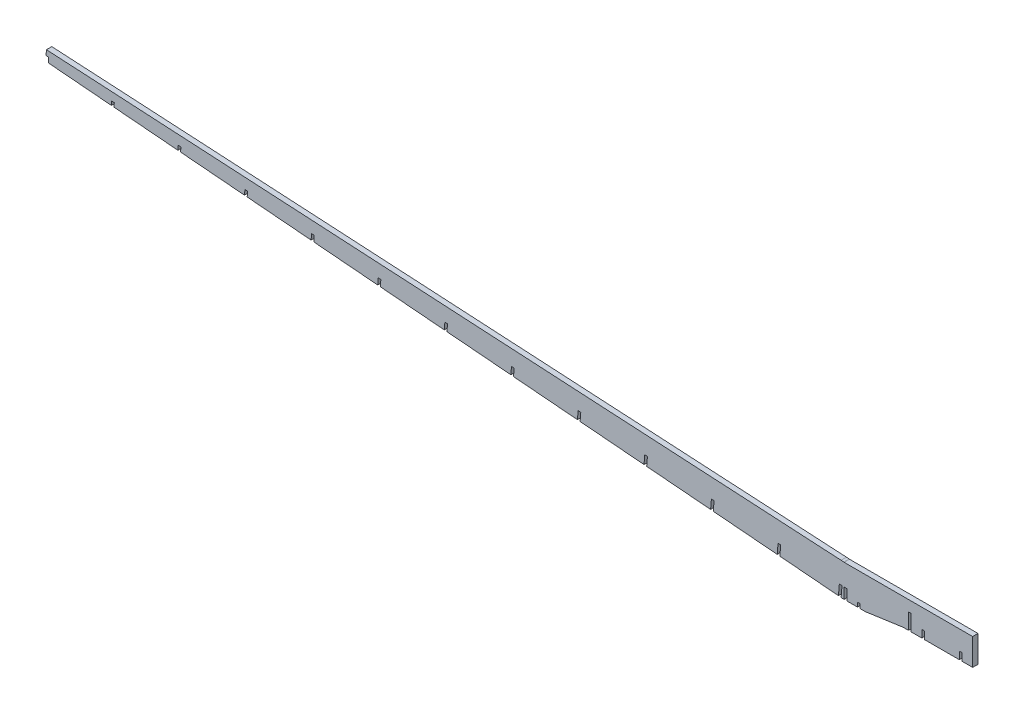
SolidWorks part; units mm, degrees
material "Balsa"
ref_plane "Front Plane" through (0, 0, 0) normal (0, 0, 1) x (1, 0, 0)
ref_plane "Top Plane" through (0, 0, 0) normal (0, 1, 0) x (1, 0, 0)
ref_plane "Right Plane" through (0, 0, 0) normal (1, 0, 0) x (0, 0, -1)
sketch "Sketch1" plane through (0, 0, 0) normal (0, 0, 1) x (1, 0, 0)
  line L0 (76.2, 56.7475) -> (76.2, 37.6975)
  line L1 (79.375, 56.7475) -> (79.375, 37.6975)
  line L2 (0, 44.0475) -> (0, 31.3475)
  line L3 (3.175, 44.0475) -> (3.175, 31.3475)
  line L4 (-5.7133, 44.4467) -> (-6.776, 31.7912)
  line L5 (-2.5494, 44.181) -> (-3.6121, 31.5255)
  line L6 (-1.4923, 31.3475) -> (25.4, 31.3475)
  line L7 (25.4, 31.3475) -> (69.85, 37.6975)
  line L8 (-2.5494, 44.181) -> (-0.424, 69.4919) construction
  line L9 (-0.424, 69.4919) -> (-3.5879, 69.7576)
  line L10 (-3.5879, 69.7576) -> (-5.7133, 44.4467) construction
  line L11 (-5.7133, 44.4467) -> (-2.5494, 44.181)
  line L12 (3.175, 44.0475) -> (3.175, 69.4475) construction
  line L13 (3.175, 69.4475) -> (0, 69.4475)
  line L14 (0, 69.4475) -> (0, 44.0475) construction
  line L15 (0, 44.0475) -> (3.175, 44.0475)
  line L16 (92.075, 37.6975) -> (92.075, 46.5875)
  line L17 (-942.8808, 122.7744) -> (-947.5199, 67.5279)
  line L18 (0, 69.4475) -> (-0.424, 69.4919)
  line L19 (3.175, 69.4475) -> (152.4, 69.4475)
  line L20 (152.4, 69.4475) -> (152.4, 37.6975)
  line L21 (152.4, 37.6975) -> (69.85, 37.6975)
  line L22 (92.075, 46.5875) -> (95.25, 46.5875)
  line L23 (95.25, 46.5875) -> (95.25, 37.6975)
  line L24 (-1.4923, 31.3475) -> (-943.9128, 110.4848)
  line L25 (79.375, 69.4475) -> (79.375, 56.7475)
  line L26 (-942.8808, 122.7744) -> (-3.5879, 69.7576)
  line L27 (136.525, 37.6975) -> (136.525, 46.5875)
  line L28 (76.2, 69.4475) -> (76.2, 56.7475)
  line L29 (79.375, 56.7475) -> (76.2, 56.7475)
  line L30 (-943.5688, 114.5813) -> (-5.7133, 44.4467)
  line L31 (136.525, 46.5875) -> (139.7, 46.5875)
  line L32 (139.7, 46.5875) -> (139.7, 37.6975)
  line L33 (15.875, 31.3475) -> (15.875, 36.4275)
  line L34 (15.875, 36.4275) -> (19.05, 36.4275)
  line L35 (19.05, 36.4275) -> (19.05, 31.3475)
  line L36 (-942.8808, 122.7744) -> (-946.0519, 122.9534)
  line L37 (-946.0519, 122.9534) -> (-946.5835, 116.6233)
  line L38 (-946.5835, 116.6233) -> (-943.4123, 116.4443)
  dimension "D3" = 76.2
  dimension "D10" = 12.3329
  dimension "D11" = 8.2219
  dimension "D2" = 25.4
  dimension "D4" = 25.4
  dimension "D5" = 12.7
  dimension "D7" = 3.175
  dimension "D9" = 3.175
  dimension "D12" = 3.175
  dimension "D6" = 19.05
  dimension "D13" = 6.35
  dimension "D14" = 12.7
  dimension "D16" = 3.175
  dimension "D17" = 3.175
  dimension "D18" = 12.7
  dimension "D19" = 12.7
  dimension "D20" = 8.89
  dimension "D21" = 8.89
  dimension "D15" = 76.2
  dimension "D22" = 12.7
  dimension "D23" = 3.175
  dimension "D24" = 5.08
  dimension "D8" = 6.35
  dimension "D25" = 3.175
  dimension "D26" = 6.35
extrude "Boss-Extrude1" add sketch "Sketch1" along normal mid plane 6.35 contours L17 L30 L11 L5 L24 L6 L2 L15 L3 L7 L21 L0 L28 L19 L13 L18 L9 L26 | L30 L17 L24 L4 | L29 L25 L19 L28 | L19 L25 L1 L21 L20 | L37 L38 L17 L36
sketch "Sketch2" plane through (0, 0, 3.175) normal (0, 0, 1) x (1, 0, 0)
  line L2 (-73.2652, 73.2231) -> (-80.3969, -11.7061)
  line L3 (-943.5688, 114.5813) -> (-5.7133, 44.4467)
  line L6 (-76.4291, 73.4888) -> (-83.5608, -11.4404)
  line L7 (-6.776, 31.7912) -> (-943.9128, 110.4848)
  line L10 (-152.4177, 77.6821) -> (-159.3225, -4.5442)
  line L14 (-155.5816, 77.9478) -> (-162.4863, -4.2785)
  line L18 (-231.5658, 82.1932) -> (-238.251, 2.5812)
  line L22 (-234.7297, 82.4589) -> (-241.4149, 2.8469)
  line L26 (-310.7178, 86.6582) -> (-317.1769, 9.7387)
  line L30 (-313.8817, 86.9239) -> (-320.3408, 10.0043)
  line L34 (-389.8657, 91.1713) -> (-396.1056, 16.8623)
  line L38 (-393.0296, 91.437) -> (-399.2695, 17.128)
  line L42 (-469.0186, 95.6263) -> (-475.031, 24.0265)
  line L46 (-472.1824, 95.892) -> (-478.1948, 24.2921)
  line L50 (-548.1666, 100.1381) -> (-553.9596, 31.1506)
  line L54 (-551.3305, 100.4038) -> (-557.1235, 31.4163)
  line L58 (-627.3195, 104.5918) -> (-632.8849, 38.3152)
  line L62 (-630.4834, 104.8575) -> (-636.0488, 38.5809)
  line L66 (-706.4673, 109.1069) -> (-711.8138, 45.4365)
  line L70 (-709.6312, 109.3725) -> (-714.9777, 45.7022)
  line L74 (-785.6206, 113.5558) -> (-790.7389, 52.6041)
  line L78 (-788.7845, 113.8214) -> (-793.9027, 52.8697)
  line L82 (-864.7684, 118.071) -> (-869.6679, 59.7246)
  line L86 (-867.9323, 118.3366) -> (-872.8317, 59.9902)
  line L89 (-942.9091, 122.4365) -> (-947.5795, 66.8182)
  line M2 (-943.9128, 110.4848) -> (-6.776, 31.7912)
extrude "Cut-Extrude1" cut sketch "Sketch2" against normal through all contours L3 L6 L2 M2 | L3 L14 L7 L10 | L3 L22 L7 L18 | L3 L30 L7 L26 | L3 L38 L7 L34 | L3 L46 L7 L42 | L3 L54 L7 L50 | L3 L62 L7 L58 | L3 L70 L7 L66 | L3 L78 L7 L74 | L3 L86 L7 L82
move or copy body "Body-Move/Copy1" [suppressed] bodies to move or copy 102 parameters "D1"=0, "D2"=0, "D3"=0
equation "\"D11@Sketch1\"=\"D10@Sketch1\"*(2/3)"
